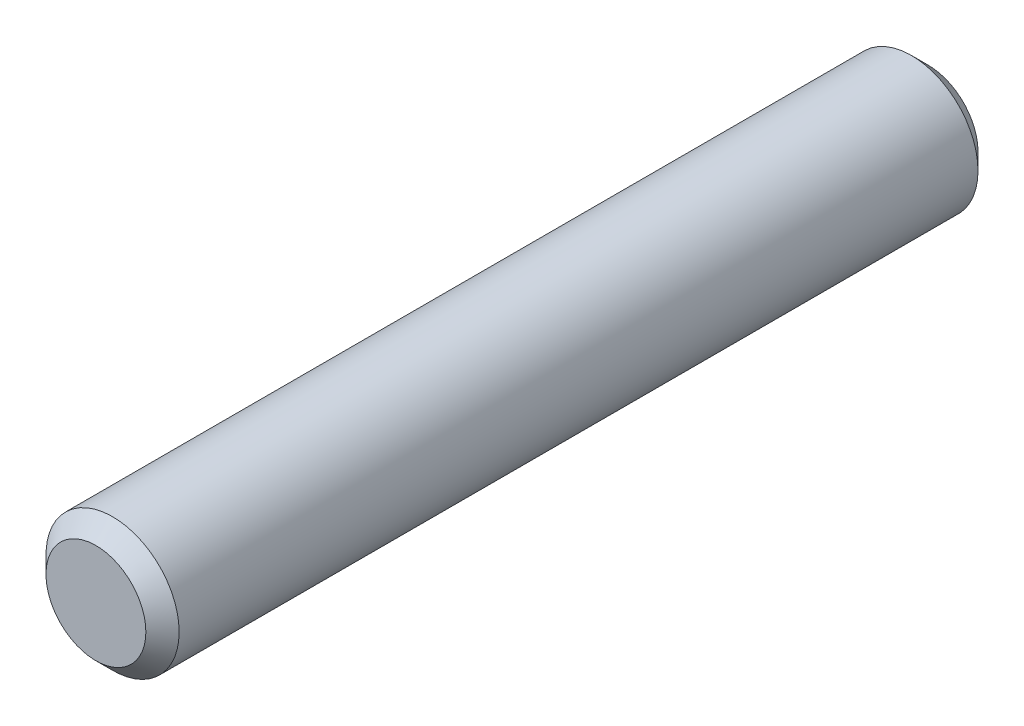
SolidWorks part; units mm, degrees
ref_plane "Piano frontale" through (0, 0, 0) normal (0, 0, 1) x (1, 0, 0)
ref_plane "Piano superiore" through (0, 0, 0) normal (0, 1, 0) x (1, 0, 0)
ref_plane "Piano destro" through (0, 0, 0) normal (1, 0, 0) x (0, 0, -1)
sketch "Schizzo1" plane through (0, 0, 0) normal (0, 0, 1) x (1, 0, 0)
  circle A0 centre (0, 0) radius 4
  dimension "D1" = 8
extrude "Estrusione-Estrusione1" add sketch "Schizzo1" along normal blind 50
chamfer "Smusso1" distance 1 angle 45 2 edges at (4, 0, 50) (4, 0, 0)
